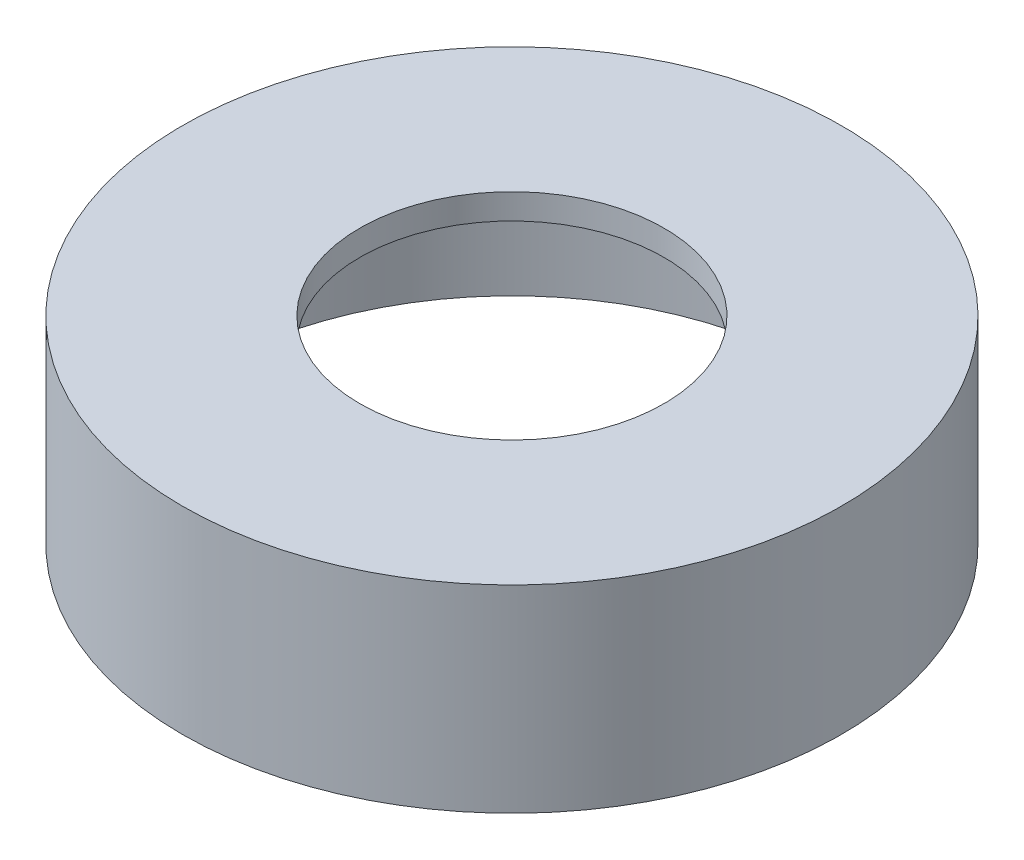
SolidWorks part; units mm, degrees
ref_plane "Alzado" through (0, 0, 0) normal (0, 0, 1) x (1, 0, 0)
ref_plane "Planta" through (0, 0, 0) normal (0, 1, 0) x (1, 0, 0)
ref_plane "Vista lateral" through (0, 0, 0) normal (1, 0, 0) x (0, 0, -1)
sketch "Croquis1" plane through (0, 0, 0) normal (0, 1, 0) x (1, 0, 0)
  circle A0 centre (0, 0) radius 32.5
  dimension "D1" = 65
extrude "Saliente-Extruir1" add sketch "Croquis1" along normal blind 19.5
shell "Vaciado1" thickness 2.5
sketch "Croquis2" plane through (0, 19.5, 0) normal (0, 1, 0) x (1, 0, 0)
  circle A0 centre (0, 0) radius 15
  dimension "D1" = 30
extrude "Cortar-Extruir1" cut sketch "Croquis2" against normal blind 19.5
sketch "Croquis3" plane through (0, 0, 0) normal (1, 0, 0) x (0, 0, -1)
  line L0 (-30, 0) -> (-30, 4) construction
  line L1 (-30, 0) -> (30, 0) construction
  line L2 (-32.5, 0) -> (32.5, 0) construction
  line L3 (-30, 4) -> (-28.1, 4)
  line L4 (-30, 4) -> (-30, 8)
  line L5 (-28.1, 4) -> (-28.1, 6)
  line L6 (-30, 8) -> (-28.1, 6)
  dimension "D1" = 4
  dimension "D2" = 1.9
  dimension "D3" = 4
  dimension "D4" = 2
extrude "Saliente-Extruir2" add sketch "Croquis3" along normal mid plane 3
pattern_circular "MatrizC2" count 4 over 360 about axis through (0, 0, 0) along (0, 1, 0) of "Saliente-Extruir2"
